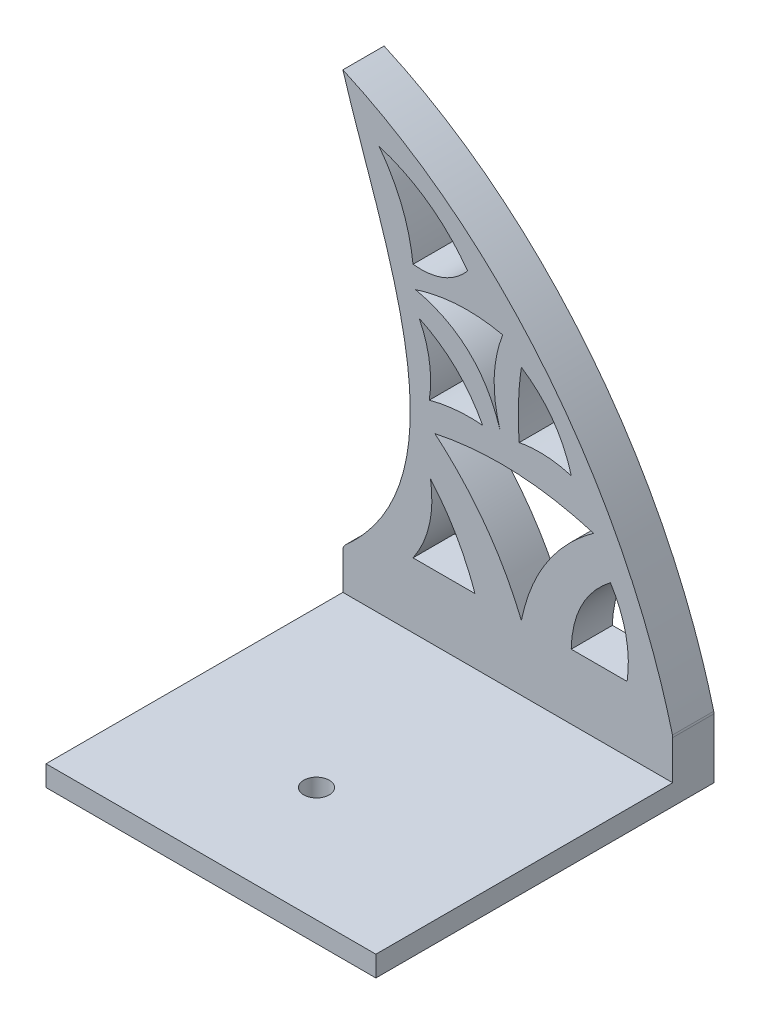
SolidWorks part; units mm, degrees
material "1060 Alloy"
ref_plane "Front Plane" through (0, 0, 0) normal (0, 0, 1) x (1, 0, 0)
ref_plane "Top Plane" through (0, 0, 0) normal (0, 1, 0) x (1, 0, 0)
ref_plane "Right Plane" through (0, 0, 0) normal (1, 0, 0) x (0, 0, -1)
sketch "Sketch1" plane through (0, 0, 0) normal (0, 0, 1) x (1, 0, 0)
  line L1 (0, 0) -> (101.6, 0)
  line L2 (0, 0) -> (0, 152.4)
  line L3 (0, 152.4) -> (101.6, 152.4)
  line L4 (101.6, 0) -> (101.6, 152.4)
  dimension "D1" = 101.6
  dimension "D2" = 152.4
extrude "Boss-Extrude1" add sketch "Sketch1" along normal blind 12.7 contours L2 L1 L4 L3
sketch "Sketch2" plane through (0, 0, 0) normal (0, 0, 1) x (1, 0, 0)
  line L0 (0, 152.4) -> (0, 279.4) construction
  line L1 (0, 152.4) -> (101.6, 152.4)
  line L3 (40.6766, 160.02) -> (21.6029, 160.02)
  line L4 (70.3278, 160.02) -> (87.5465, 160.02)
  spline S0 degree 3 poles (0, 279.4) (51.2861, 256.55) (87.8369, 205.9579) (101.6, 152.4) knots 0 0 0 0 1 1 1 1
  spline S1 degree 3 poles (0, 152.4) (39.7901, 186.8391) (12.3098, 238.8455) (0, 279.4) knots 0 0 0 0 1 1 1 1
  spline S2 degree 2 poles (26.9805, 183.8137) (28.9588, 170.8375) (21.6029, 160.02) knots 0 0 0 1 1 1
  spline S3 degree 2 poles (82.3961, 183.8137) (89.3396, 172.7738) (87.5465, 160.02) knots 0 0 0 1 1 1
  spline S4 degree 2 poles (23.5161, 224.8619) (28.2353, 215.2193) (26.6057, 204.5822) knots 0 0 0 1 1 1
  spline S5 degree 2 poles (54.9771, 227.5573) (66.6459, 219.8522) (70.3283, 206.2775) knots 0 0 0 1 1 1
  spline S6 degree 2 poles (21.6029, 238.3231) (31.8648, 237.2845) (38.4123, 244.9499) knots 0 0 0 1 1 1
  spline S7 degree 2 poles (26.9805, 183.8137) (36.1385, 173.1751) (40.6766, 160.02) knots 0 0 0 1 1 1
  spline S8 degree 2 poles (82.3961, 183.8137) (70.6714, 174.6636) (70.3278, 160.02) knots 0 0 0 1 1 1
  spline S9 degree 2 poles (54.9771, 160.02) (46.0835, 181.5476) (28.3421, 196.5298) knots 0 0 0 1 1 1
  spline S10 degree 2 poles (54.9771, 160.02) (59.3747, 181.4006) (77.1872, 194.3635) knots 0 0 0 1 1 1
  spline S11 degree 2 poles (28.3421, 196.5298) (53.0178, 201.7323) (77.1872, 194.3635) knots 0 0 0 1 1 1
  spline S12 degree 2 poles (26.6057, 204.5822) (34.7004, 206.7929) (43.0535, 206.088) knots 0 0 0 1 1 1
  spline S13 degree 2 poles (43.0535, 206.088) (36.2398, 218.9127) (23.5161, 224.8619) knots 0 0 0 1 1 1
  spline S14 degree 2 poles (70.3283, 206.2775) (62.3616, 208.669) (54.2871, 207.1099) knots 0 0 0 1 1 1
  spline S15 degree 2 poles (54.2871, 207.1099) (53.4821, 217.3917) (54.9771, 227.5573) knots 0 0 0 1 1 1
  spline S16 degree 2 poles (48.4004, 207.5354) (42.0542, 227.5662) (22.3756, 231.9373) knots 0 0 0 1 1 1
  spline S17 degree 2 poles (48.4004, 207.5354) (44.3936, 220.7345) (49.2258, 233.3158) knots 0 0 0 1 1 1
  spline S18 degree 2 poles (49.2258, 233.3158) (35.6412, 236.2679) (22.3756, 231.9373) knots 0 0 0 1 1 1
  spline S19 degree 2 poles (21.6029, 238.3231) (19.952, 252.9745) (11.0947, 264.6015) knots 0 0 0 1 1 1
  spline S20 degree 2 poles (11.0947, 264.6015) (28.0538, 259.2958) (38.4123, 244.9499) knots 0 0 0 1 1 1
  dimension "D1" = 127
extrude "Boss-Extrude3" add sketch "Sketch2" along normal blind 12.7 contours S1 L1 S0 S18 S17 S16 S13 S12 S4 S8 S3 L4 S2 S7 L3 S9 S11 S10 S14 S15 S5 S19 S20 S6
fillet "Fillet1" radius 2.54 2 edges at (101.6, 152.4, 6.35) (0, 152.4, 6.35)
fillet "Fillet2" radius 5.08 2 edges at (101.6, 0, 6.35) (0, 0, 6.35)
sketch "Sketch5" plane through (0, 0, 12.7) normal (0, 0, 1) x (1, 0, 0)
  line L1 (101.519, 133.6639) -> (101.6, 133.6639)
  line L2 (101.6, 5.08) -> (101.6, 152.0778) construction
  line L4 (101.6, 133.6639) -> (0, 133.6639)
  line L5 (101.6, 133.6639) -> (101.6, 0)
  line L6 (101.6, 0) -> (0, 0)
  line L7 (0, 133.6639) -> (0, 0)
  line M2 (5.08, 0) -> (96.52, 0)
  arc M3 (96.52, 0) -> (101.6, 5.08) centre (96.52, 5.08) ccw
  line M4 (101.6, 5.08) -> (101.6, 152.0778)
  line M9 (0, 151.2513) -> (0, 5.08)
  arc M10 (0, 5.08) -> (5.08, 0) centre (5.08, 5.08) ccw
extrude "Cut-Extrude2" cut sketch "Sketch5" against normal through all contours L1 L4 M9 M10 M2 M3 M4
sketch "Sketch8" plane through (0, 0, 12.7) normal (0, 0, 1) x (1, 0, 0)
  line L0 (0, 133.6639) -> (0, 151.2513) construction
  line L1 (101.6, 133.6639) -> (0, 133.6639)
  line L2 (101.6, 133.6639) -> (101.6, 140.0139)
  line L3 (101.6, 140.0139) -> (0, 140.0139)
  line L4 (0, 133.6639) -> (0, 140.0139)
  dimension "D1" = 6.35
extrude "Boss-Extrude4" add sketch "Sketch8" along normal blind 91.44
sketch "Sketch9" plane through (0, 140.0139, 0) normal (0, 1, 0) x (1, 0, 0)
  line L0 (101.6, -12.7) -> (0, -12.7) construction
  line L3 (101.6, -104.14) -> (101.6, -12.7) construction
  circle A1 centre (48.006, -68.834) radius 3.937
  dimension "D1" = 7.874
  dimension "D2" = 56.134
  dimension "D3" = 53.594
extrude "Cut-Extrude3" cut sketch "Sketch9" against normal through all
